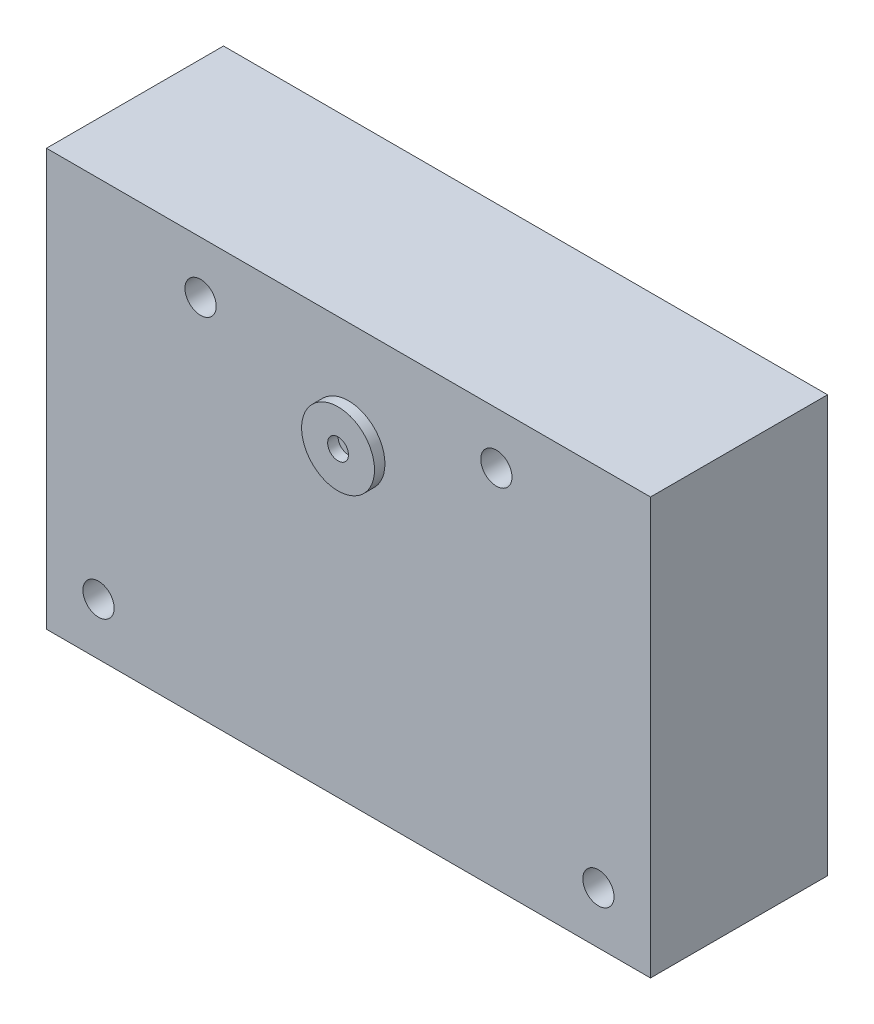
SolidWorks part; units mm, degrees
ref_plane "前视基准面" through (0, 0, 0) normal (0, 0, 1) x (1, 0, 0)
ref_plane "上视基准面" through (0, 0, 0) normal (0, 1, 0) x (1, 0, 0)
ref_plane "右视基准面" through (0, 0, 0) normal (1, 0, 0) x (0, 0, -1)
sketch "草图1" plane through (0, 0, 0) normal (0, 0, 1) x (1, 0, 0)
  line L1 (-29, 20) -> (29, 20)
  line L2 (-29, 20) -> (-29, -20)
  line L3 (-29, -20) -> (29, -20)
  line L4 (29, 20) -> (29, -20)
  line L5 (-29, 20) -> (29, -20) construction
  line L6 (-29, -20) -> (29, 20) construction
  point P0 (0, 0)
  dimension "D1" = 58
  dimension "D2" = 40
extrude "凸台-拉伸1" add sketch "草图1" along normal blind 17
sketch "草图2" plane through (0, 0, 17) normal (0, 0, 1) x (1, 0, 0)
  line L0 (-24, -15) -> (24, -15) construction
  line L1 (0, -15) -> (0, -20) construction
  line L2 (-29, -20) -> (29, -20) construction
  line L3 (-14.2, 15) -> (14.2, 15) construction
  line L4 (0, 15) -> (0, -15) construction
  circle A0 centre (-24, -15) radius 1.5
  circle A1 centre (24, -15) radius 1.5
  circle A2 centre (-14.2, 15) radius 1.5
  circle A3 centre (14.2, 15) radius 1.5
  dimension "D3" = 3
  dimension "D1" = 5
  dimension "D2" = 48
  dimension "D4" = 28.4
  dimension "D5" = 30
extrude "切除-拉伸1" cut sketch "草图2" against normal blind 5
sketch "草图3" plane through (0, 0, 0) normal (0, 0, -1) x (-1, 0, 0)
  line L0 (-29, -20) -> (-29, 20) construction
  line L1 (-26, 17) -> (17, 17)
  line L2 (-26, 17) -> (-26, -17)
  line L3 (-26, -17) -> (17, -17)
  line L4 (17, 17) -> (17, -17)
  line L5 (-29, 20) -> (29, 20) construction
  line L6 (29, -20) -> (-29, -20) construction
  line L7 (29, 20) -> (29, -20) construction
  point P4 (-24.1742, 16.6216)
  point P5 (15.9253, -16.4569)
  dimension "D1" = 3
  dimension "D2" = 3
  dimension "D3" = 3
  dimension "D4" = 12
extrude "切除-拉伸2" cut sketch "草图3" against normal blind 0.5
sketch "草图4" plane through (0, 0, 17) normal (0, 0, 1) x (1, 0, 0)
  line L0 (0, 20) -> (0, 10) construction
  line L1 (29, 20) -> (-29, 20) construction
  circle A0 centre (0, 10) radius 3.5
  circle A1 centre (0, 10) radius 1
  dimension "D2" = 7
  dimension "D3" = 2
  dimension "D1" = 10
extrude "凸台-拉伸2" add sketch "草图4" along normal blind 1
